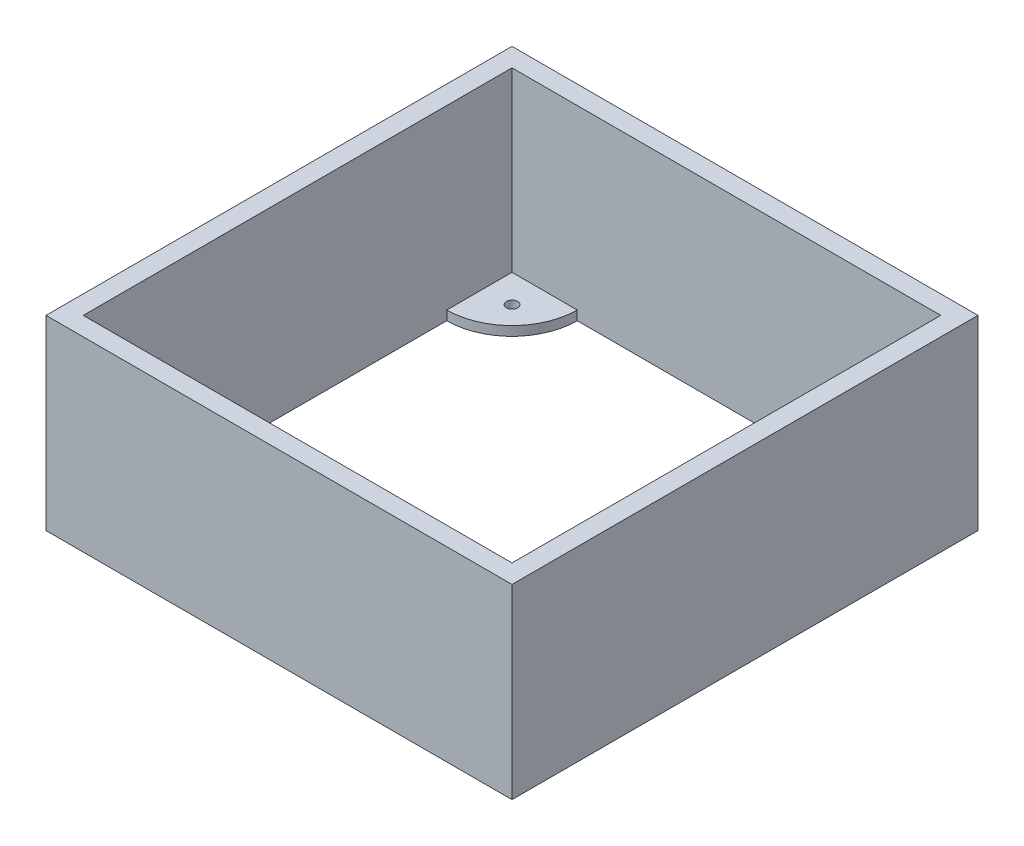
SolidWorks part; units mm, degrees
ref_plane "Front Plane" through (0, 0, 0) normal (0, 0, 1) x (1, 0, 0)
ref_plane "Top Plane" through (0, 0, 0) normal (0, 1, 0) x (1, 0, 0)
ref_plane "Right Plane" through (0, 0, 0) normal (1, 0, 0) x (0, 0, -1)
sketch "Sketch1" plane through (0, 0, 0) normal (0, 1, 0) x (1, 0, 0)
  line L1 (-50, -50) -> (50, -50)
  line L2 (-50, -50) -> (-50, 50)
  line L3 (-50, 50) -> (50, 50)
  line L4 (50, -50) -> (50, 50)
  line L5 (-50, -50) -> (50, 50) construction
  line L6 (-50, 50) -> (50, -50) construction
  line L7 (-46, 46) -> (46, 46)
  line L8 (-46, 46) -> (-46, -46)
  line L9 (-46, -46) -> (46, -46)
  line L10 (46, 46) -> (46, -46)
  line L11 (-46, 46) -> (46, -46) construction
  line L12 (-46, -46) -> (46, 46) construction
  point P0 (0, 0)
  point P6 (0, 0)
  dimension "D1" = 4
  dimension "D2" = 100
  dimension "D3" = 100
extrude "Boss-Extrude1" add sketch "Sketch1" along normal blind 40
sketch "Sketch2" plane through (0, 0, 0) normal (0, -1, 0) x (-1, 0, 0)
  line L0 (-46, 32) -> (-46, 46)
  line L1 (-46, 46) -> (-32, 46)
  line L2 (32, 46) -> (46, 46)
  line L3 (46, 46) -> (46, 32)
  line L4 (46, -32) -> (46, -46)
  line L5 (46, -46) -> (32, -46)
  line L6 (-32, -46) -> (-46, -46)
  line L7 (-46, -46) -> (-46, -32)
  arc A0 (-46, 32) -> (-32, 46) centre (-46, 46) ccw
  arc A1 (32, 46) -> (46, 32) centre (46, 46) ccw
  arc A2 (46, -32) -> (32, -46) centre (46, -46) ccw
  arc A3 (-32, -46) -> (-46, -32) centre (-46, -46) ccw
  point P16 (0, 0)
  dimension "D2" = 14
  dimension "D1" = 4
extrude "Boss-Extrude2" add sketch "Sketch2" against normal blind 2
sketch "Sketch3" plane through (0, 0, 0) normal (0, -1, 0) x (-1, 0, 0)
  line L0 (-32, 46) -> (32, 46) construction
  line L1 (-46, -32) -> (-46, 32) construction
  line L2 (46, 32) -> (46, -32) construction
  line L3 (32, -46) -> (-32, -46) construction
  point P0 (-40, 40)
  point P1 (40, 40)
  point P2 (40, -40)
  point P3 (-40, -40)
  point P6 (0, 0)
  point P7 (0, 0)
  point P8 (0, 0)
  point P11 (0, 0)
  point P14 (0, 0)
  dimension "D2" = 6
  dimension "D1" = 6
  dimension "D3" = 6
  dimension "D4" = 6
  dimension "D5" = 6
  dimension "D6" = 6
  dimension "D7" = 6
  dimension "D8" = 6
hole_wizard "M2 Clearance Hole1" positions "3DSketch1" profile "Sketch4" hole size "M2" standard "ANSI Metric" end condition through all
sketch3d "3DSketch1"
  point P0 (40, 0, 40)
  point P3 (40, 0, -40)
  point P6 (-40, 0, -40)
  point P9 (-40, 0, 40)
sketch "Sketch4" plane through (40, 0, 40) normal (1, 0, 0) x (0, 0, -1)
  line L0 (0, 0) -> (0, 40)
  line L1 (0, 40) -> (1.2, 40)
  line L2 (1.2, 40) -> (1.2, 0)
  line L5 (1.2, 0) -> (0, 0)
  line L11 (0, -6.35) -> (0, 107.95) construction
  dimension "Thru Hole Dia." = 2.4
  dimension "Thru Hole Depth" = 40
